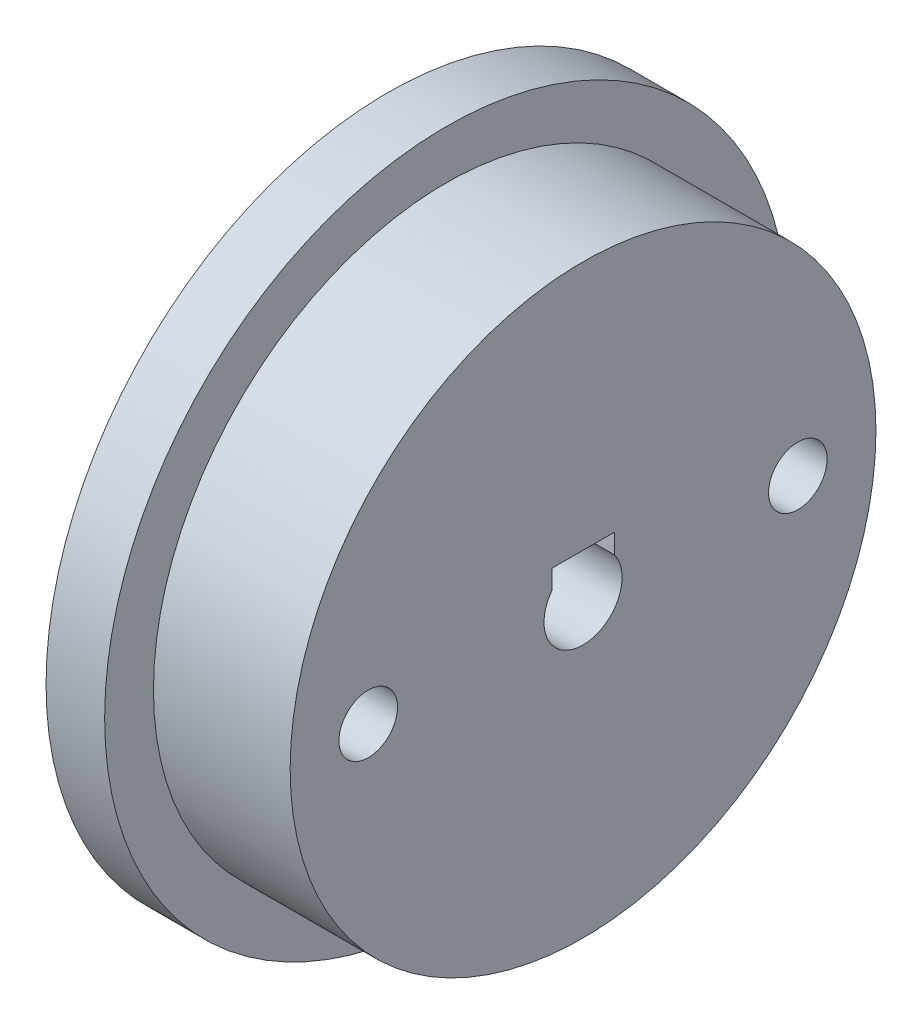
SolidWorks part; units mm, degrees
ref_plane "Front Plane" through (0, 0, 0) normal (0, 0, 1) x (1, 0, 0)
ref_plane "Top Plane" through (0, 0, 0) normal (0, 1, 0) x (1, 0, 0)
ref_plane "Right Plane" through (0, 0, 0) normal (1, 0, 0) x (0, 0, -1)
sketch "Sketch1" plane through (0, 0, 0) normal (0, 0, 1) x (1, 0, 0)
  line L0 (0, 0) -> (24.4828, 0) construction
  line L1 (0, 0) -> (0, 17.5)
  line L2 (0, 17.5) -> (3, 17.5)
  line L3 (3, 17.5) -> (3, 15)
  line L4 (3, 15) -> (10, 15)
  line L5 (10, 15) -> (10, 0)
  line L6 (0, 0) -> (10, 0)
  dimension "D1" = 10
  dimension "D2" = 15
  dimension "D3" = 17.5
  dimension "D4" = 3
revolve "Revolve1" add sketch "Sketch1" angle 360 about L0
sketch "Sketch2" plane through (10, 0, 0) normal (1, 0, 0) x (0, 0, -1)
  line L0 (0, 0) -> (0, 4.9467) construction
  line L2 (-1.6, 1.2) -> (-1.6, 2.2)
  line L3 (1.6, 1.2) -> (1.6, 2.2)
  line L4 (-1.6, 2.2) -> (1.6, 2.2)
  line L5 (0, 0) -> (-11, 0) construction
  arc A0 (-1.6, 1.2) -> (1.6, 1.2) centre (0, 0) ccw
  circle A1 centre (-11, 0) radius 1.5
  circle A2 centre (11, 0) radius 1.5
  dimension "D1" = 2
  dimension "D3" = 3
  dimension "D4" = 11
  dimension "D2" = 3.2
  dimension "D5" = 1
extrude "Cut-Extrude1" cut sketch "Sketch2" against normal through all
